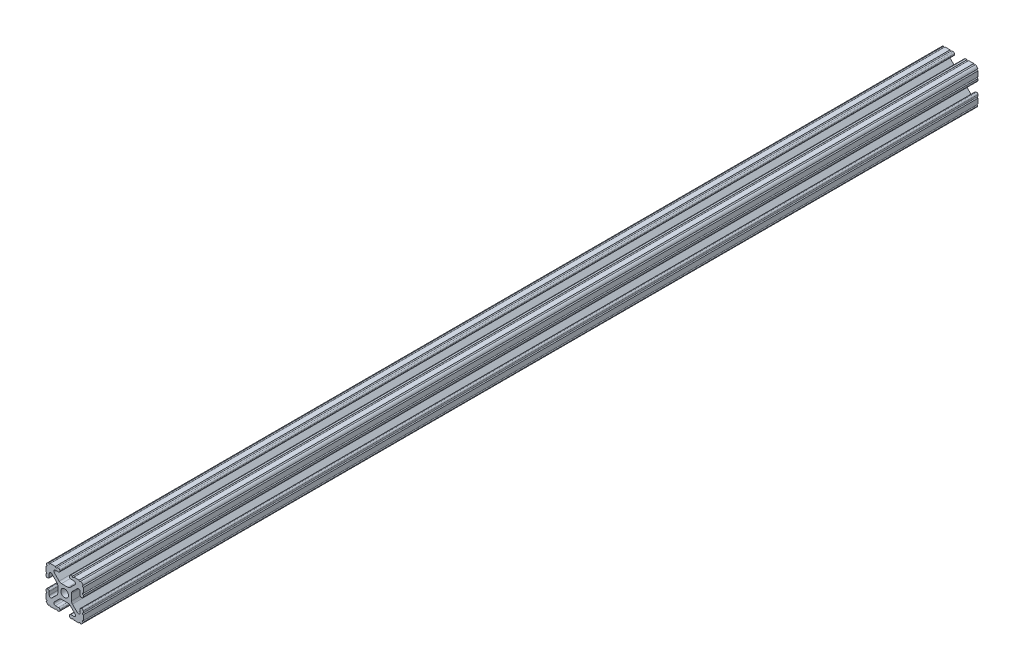
SolidWorks part; units mm, degrees
ref_plane "Front Plane" through (0, 0, 0) normal (0, 0, 1) x (1, 0, 0)
ref_plane "Top Plane" through (0, 0, 0) normal (0, 1, 0) x (1, 0, 0)
ref_plane "Right Plane" through (0, 0, 0) normal (1, 0, 0) x (0, 0, -1)
sketch "Sketch2" plane through (0, 0, 0) normal (0, 0, 1) x (1, 0, 0)
  line L0 (0, 12.7) -> (0, -12.7) construction
  line L1 (-12.7, 0) -> (12.7, 0) construction
  line L2 (3.2512, -12.7) -> (12.7, -12.7)
  line L3 (12.7, -12.7) -> (12.7, -3.2512)
  line L4 (3.2512, -12.7) -> (3.2512, -10.4902)
  line L5 (3.2512, -10.4902) -> (8.9276, -10.4902)
  line L6 (8.9276, -10.4902) -> (3.0856, -4.6482)
  line L7 (0, 0) -> (12.7, -12.7) construction
  line L8 (12.7, -3.2512) -> (10.4902, -3.2512)
  line L9 (10.4902, -3.2512) -> (10.4902, -8.9276)
  line L10 (10.4902, -8.9276) -> (4.6482, -3.0856)
  circle A0 centre (0, 0) radius 2.6035
  arc A1 (6.3485, -10.4902) -> (7.1039, -8.6665) centre (6.3485, -9.4219) ccw construction
  point P8 (0, -4.6482)
  dimension "Center Hole Diameter" = 5.207
  dimension "Rail Height" = 25.4
  dimension "Rail Width" = 25.4
  dimension "T-Slot Width" = 6.5024
  dimension "Slot Inner Width" = 14.8336
  dimension "Thickness" = 2.2098
  dimension "Slot Depth" = 5.842
  dimension "D1" = 2.2098
sketch "Sketch3" plane through (0, 0, 0) normal (1, 0, 0) x (0, 0, -1)
  line L0 (-304.8, -12.7) -> (304.8, -12.7) construction
  line L1 (-279.4, 0) -> (279.4, 0) construction
  dimension "Length" = 609.6
  dimension "D1" = 25.4
sketch "Sketch4" plane through (0, 0, 0) normal (0, 0, 1) x (1, 0, 0)
  line L0 (4.1904, -12.7) -> (10.1173, -12.7)
  line L1 (3.2512, -12.7) -> (12.7, -12.7) construction
  line L2 (3.2512, -12.7) -> (3.2512, -10.4902) construction
  line L3 (3.2512, -10.4902) -> (8.9276, -10.4902) construction
  line L4 (3.2512, -11.4294) -> (3.2512, -11.7608)
  line L5 (4.1904, -10.4902) -> (6.3485, -10.4902)
  line L6 (0, -4.6482) -> (2.164, -4.6482)
  line L7 (8.9276, -10.4902) -> (3.0856, -4.6482) construction
  line L8 (3.7373, -5.2999) -> (7.1039, -8.6665)
  line L9 (12.7, -12.7) -> (12.7, -3.2512) construction
  line L10 (10.4902, -8.9276) -> (4.6482, -3.0856) construction
  line L11 (10.4902, -3.2512) -> (10.4902, -8.9276) construction
  line L12 (10.4902, -6.3485) -> (10.4902, -4.1904)
  line L13 (12.7, -3.2512) -> (10.4902, -3.2512) construction
  line L14 (11.4294, -3.2512) -> (11.7608, -3.2512)
  line L15 (12.7, -4.1904) -> (12.7, -10.1173)
  line L16 (8.6665, -7.1039) -> (5.2999, -3.7373)
  line L17 (4.6482, 0) -> (4.6482, -2.164)
  line L18 (-12.7, 0) -> (12.7, 0) construction
  line L19 (0, -4.6482) -> (0, -2.6035)
  line L20 (0, 12.7) -> (0, -12.7) construction
  line L21 (4.6482, 0) -> (2.6035, 0)
  arc A0 (3.2512, -11.7608) -> (4.1904, -12.7) centre (4.1904, -11.7608) ccw
  arc A2 (3.2512, -11.4294) -> (4.1904, -10.4902) centre (4.1904, -11.4294) cw
  arc A3 (6.3485, -10.4902) -> (7.1039, -8.6665) centre (6.3485, -9.4219) ccw
  arc A4 (2.164, -4.6482) -> (3.7373, -5.2999) centre (2.164, -6.8732) cw
  arc A5 (10.1173, -12.7) -> (12.7, -10.1173) centre (10.1173, -10.1173) ccw
  arc A6 (8.6665, -7.1039) -> (10.4902, -6.3485) centre (9.4219, -6.3485) ccw
  arc A7 (10.4902, -4.1904) -> (11.4294, -3.2512) centre (11.4294, -4.1904) cw
  arc A8 (11.7608, -3.2512) -> (12.7, -4.1904) centre (11.7608, -4.1904) cw
  arc A9 (5.2999, -3.7373) -> (4.6482, -2.164) centre (6.8732, -2.164) cw
  circle A10 centre (0, 0) radius 2.6035 construction
  arc A11 (0, -2.6035) -> (2.6035, 0) centre (0, 0) ccw
  dimension "D1" = 2.5827
  dimension "D2" = 2.225
  dimension "D3" = 0.9392
extrude "Boss-Extrude1" add sketch "Sketch4" along normal mid plane 609.6
sketch "Sketch5" plane through (0, 0, 0) normal (0, 0, 1) x (1, 0, 0)
  line L0 (3.2512, -12.7) -> (12.7, -12.7) construction
  line L1 (4.1904, -10.4902) -> (6.3485, -10.4902) construction
  line L3 (0, 0) -> (12.7, -12.7) construction
  line L4 (6.3485, -10.4902) -> (6.3485, -12.7) construction
  line L5 (8.9276, -10.4902) -> (3.0856, -4.6482) construction
  circle A0 centre (10.3562, -12.7) radius 0.5524
  circle A1 centre (5.796, -12.7) radius 0.5524
  circle A2 centre (12.7, -10.3562) radius 0.5524
  circle A3 centre (12.7, -5.796) radius 0.5524
  point P10 (5.2694, -10.4902)
  point P12 (9.4219, -6.3485)
  dimension "D1" = 1.1049
extrude "Cut-Extrude1" cut sketch "Sketch5" against normal through all both and the other way through all
mirror "Mirror1" about plane through (0, 0, 0) normal (1, 0, 0) of bodies 137 134
mirror "Mirror2" about plane through (0, 0, 0) normal (0, 1, 0) of bodies 135
sketch "Sketch6" plane through (0, 4.6482, 0) normal (0, 1, 0) x (1, 0, 0)
  line L0 (-2.164, 304.8) -> (2.164, 304.8) construction
  line L1 (0, 192.7723) -> (0, -328.799) construction
  line L3 (0, 304.8) -> (0, 192.7723) construction
  circle A0 centre (0, 127) radius 2.6035
  circle A1 centre (0, 50.8) radius 2.6035
  circle A2 centre (0, -279.4) radius 2.6035
  dimension "D1" = 5.207
  dimension "D3" = 5.207
  dimension "D5" = 5.207
  dimension "D2" = 177.8
  dimension "D4" = 76.2
  dimension "D6" = 330.2
extrude "Cut-Extrude2" cut sketch "Sketch6" against normal blind 71.628 and the other way blind 31.496
equation "\"D1@Boss-Extrude1\"=\"Length@Sketch3\""
equation "\"D1@Sketch2\"=\"Thickness@Sketch2\""
equation "\"D2@Sketch4\"=\"Slot Inner Width@Sketch2\"*0.15"
equation "\"D1@Sketch4\"=\"D3@Sketch4\"*2.75"
equation "\"D3@Sketch4\"=\"Thickness@Sketch2\"*0.425"
equation "\"D1@Sketch5\"=\"Thickness@Sketch2\"*0.5"
